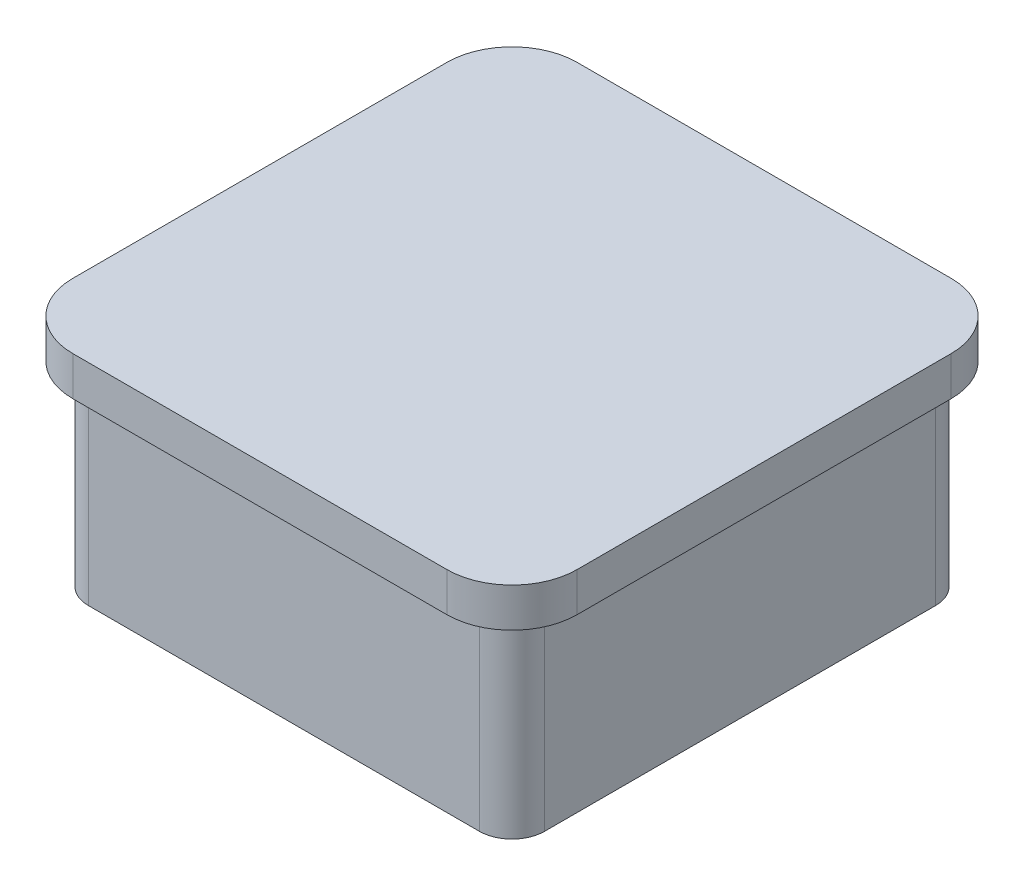
SolidWorks part; units mm, degrees
material "ABS"
ref_plane "Płaszczyzna przednia" through (0, 0, 0) normal (0, 0, 1) x (1, 0, 0)
ref_plane "Płaszczyzna górna" through (0, 0, 0) normal (0, 1, 0) x (1, 0, 0)
ref_plane "Płaszczyzna prawa" through (0, 0, 0) normal (1, 0, 0) x (0, 0, -1)
sketch "Szkic1" plane through (0, 0, 0) normal (0, 1, 0) x (1, 0, 0)
  line L1 (-38.7, -38.7) -> (38.7, -38.7)
  line L2 (-38.7, -38.7) -> (-38.7, 38.7)
  line L3 (-38.7, 38.7) -> (38.7, 38.7)
  line L4 (38.7, -38.7) -> (38.7, 38.7)
  line L5 (-38.7, -38.7) -> (38.7, 38.7) construction
  line L6 (-38.7, 38.7) -> (38.7, -38.7) construction
  point P0 (0, 0)
  dimension "D1" = 77.4
extrude "Dodanie-wyciągnięcie1" add sketch "Szkic1" against normal blind 6
sketch "Szkic2" plane through (0, -6, 0) normal (0, -1, 0) x (1, 0, 0)
  line L0 (-33, -30) -> (-33, 30)
  line L1 (-30, -35) -> (30, -35)
  line L2 (-35, -30) -> (-35, 30)
  line L3 (-30, 35) -> (30, 35)
  line L4 (35, -30) -> (35, 30)
  line L5 (-35, -35) -> (35, 35) construction
  line L6 (-35, 35) -> (35, -35) construction
  line L7 (-30, 33) -> (30, 33)
  line L8 (33, -30) -> (33, 30)
  line L9 (-30, -33) -> (30, -33)
  arc A0 (-30, 35) -> (-35, 30) centre (-30, 30) ccw
  arc A1 (35, 30) -> (30, 35) centre (30, 30) ccw
  arc A2 (-35, -30) -> (-30, -35) centre (-30, -30) ccw
  arc A3 (35, -30) -> (30, -35) centre (30, -30) cw
  arc A4 (-30, 33) -> (-33, 30) centre (-30, 30) ccw
  arc A5 (33, 30) -> (30, 33) centre (30, 30) ccw
  arc A6 (33, -30) -> (30, -33) centre (30, -30) cw
  arc A7 (-33, -30) -> (-30, -33) centre (-30, -30) ccw
  point P0 (0, 0)
  dimension "D2" = 5
  dimension "D3" = 5
  dimension "D4" = 5
  dimension "D1" = 70
  dimension "D5" = 2
extrude "Dodanie-wyciągnięcie2" add sketch "Szkic2" along normal blind 30
fillet "Zaokrąglenie1" radius 10 4 edges at (-38.7, -3, -38.7) (38.7, -3, -38.7) (38.7, -3, 38.7) (-38.7, -3, 38.7)
